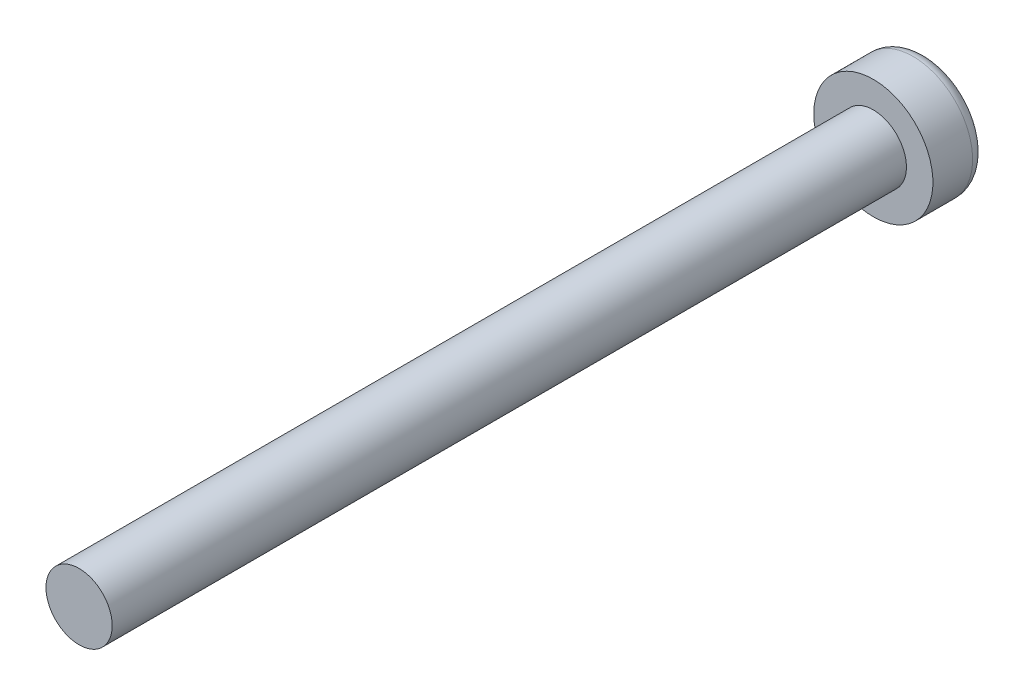
SolidWorks part; units mm, degrees
ref_plane "Front Plane" through (0, 0, 0) normal (0, 0, 1) x (1, 0, 0)
ref_plane "Top Plane" through (0, 0, 0) normal (0, 1, 0) x (1, 0, 0)
ref_plane "Right Plane" through (0, 0, 0) normal (1, 0, 0) x (0, 0, -1)
sketch "Sketch2" plane through (0, 0, 0) normal (0, 0, 1) x (1, 0, 0)
  circle A0 centre (0, 0) radius 2.5
extrude "Boss-Extrude1" add sketch "Sketch2" along normal blind 60
sketch "Sketch3" plane through (0, 0, 0) normal (0, 0, -1) x (-1, 0, 0)
  circle A0 centre (0, 0) radius 4.5
extrude "Boss-Extrude2" add sketch "Sketch3" along normal blind 4
fillet "Fillet2" radius 1 1 edges at (-4.5, 0, -4)
